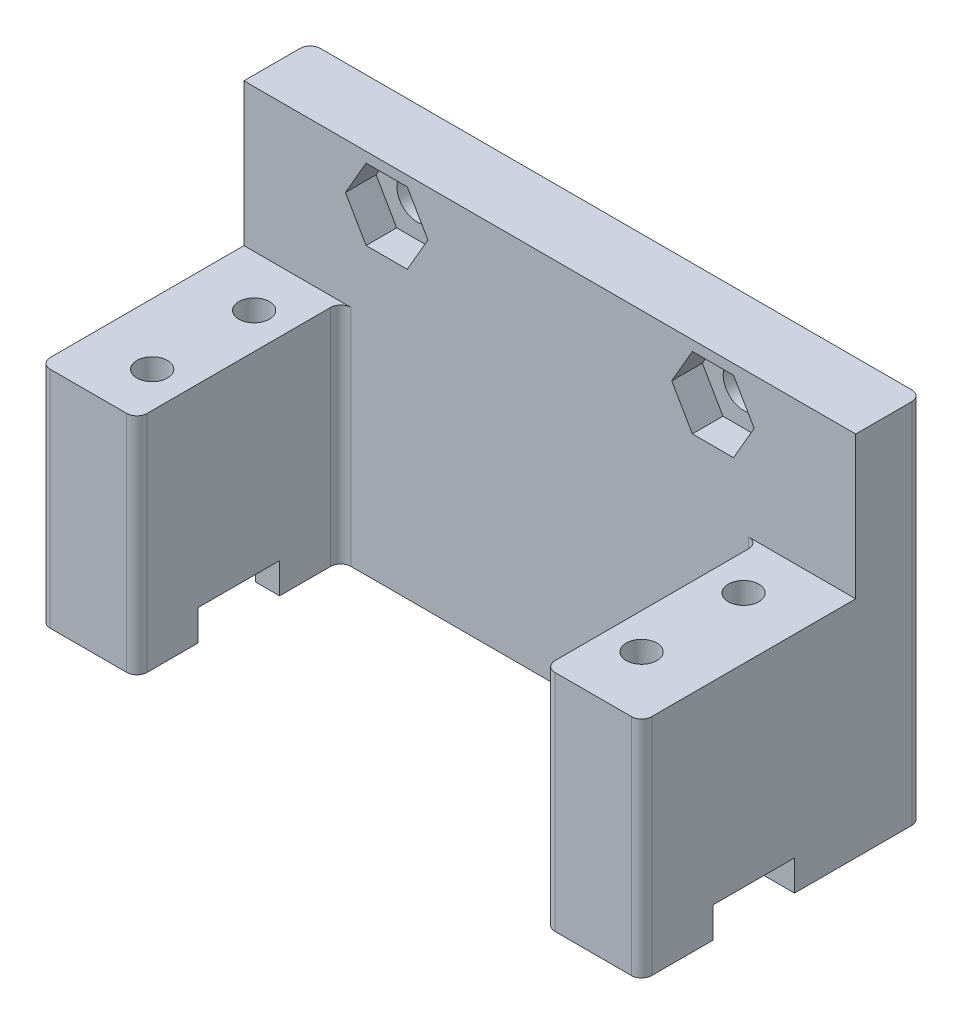
SolidWorks part; units mm, degrees
ref_plane "Front Plane" through (0, 0, 0) normal (0, 0, 1) x (1, 0, 0)
ref_plane "Top Plane" through (0, 0, 0) normal (0, 1, 0) x (1, 0, 0)
ref_plane "Right Plane" through (0, 0, 0) normal (1, 0, 0) x (0, 0, -1)
sketch "Sketch1" plane through (0, 0, 0) normal (0, 0, 1) x (1, 0, 0)
  line L1 (0, 0) -> (60, 0)
  line L2 (0, 0) -> (0, -36)
  line L3 (0, -36) -> (60, -36)
  line L4 (60, 0) -> (60, -36)
  circle A0 centre (14, -4.5) radius 2
  circle A1 centre (46, -4.5) radius 2
  dimension "D3" = 4.5
  dimension "D6" = 4
  dimension "D1" = 60
  dimension "D2" = 36
  dimension "D4" = 14
  dimension "D5" = 2
extrude "Boss-Extrude1" add sketch "Sketch1" along normal blind 6.5
sketch "Sketch2" plane through (0, -36, 0) normal (0, -1, 0) x (1, 0, 0)
  line L1 (0, 6.5) -> (9.5, 6.5)
  line L2 (0, 6.5) -> (0, 26.5)
  line L3 (0, 26.5) -> (9.5, 26.5)
  line L4 (9.5, 6.5) -> (9.5, 26.5)
  line L5 (60, 6.5) -> (50.5, 6.5)
  line L6 (60, 6.5) -> (60, 27.5)
  line L7 (60, 27.5) -> (50.5, 27.5)
  line L8 (50.5, 6.5) -> (50.5, 27.5)
  dimension "D1" = 41
  dimension "D2" = 9.5
  dimension "D3" = 20
extrude "Boss-Extrude2" add sketch "Sketch2" against normal blind 22
sketch "Sketch3" plane through (0, -14, 0) normal (0, 1, 0) x (1, 0, 0)
  line L0 (60, -6.5) -> (0, -6.5) construction
  line L1 (0, -26.5) -> (0, -6.5) construction
  circle A0 centre (6, -11.5) radius 1.5
  circle A1 centre (54, -11.5) radius 1.5
  circle A2 centre (54, -21.5) radius 1.5
  circle A3 centre (6, -21.5) radius 1.5
  dimension "D1" = 2
  dimension "D3" = 5
  dimension "D4" = 6
  dimension "D2" = 2
extrude "Cut-Extrude1" cut sketch "Sketch3" against normal up to next
sketch "Sketch4" plane through (0, 0, 6.5) normal (0, 0, 1) x (1, 0, 0)
  line L1 (11.9793, -1) -> (9.9585, -4.5)
  line L2 (9.9585, -4.5) -> (11.9793, -8)
  line L3 (11.9793, -8) -> (16.0207, -8)
  line L4 (16.0207, -8) -> (18.0415, -4.5)
  line L5 (18.0415, -4.5) -> (16.0207, -1)
  line L6 (16.0207, -1) -> (11.9793, -1)
  circle A0 centre (14, -4.5) radius 3.5 construction
  dimension "D1" = 7
extrude "Cut-Extrude2" cut sketch "Sketch4" against normal blind 3
pattern_linear "LPattern1" count 2 spacing 32 along (1, 0, 0) of "Cut-Extrude2"
fillet "Fillet1" radius 1 8 edges at (50.5, -25, 27.5) (60, -25, 27.5) (9.5, -25, 26.5) (0, -25, 26.5) (50.5, -25, 6.5) (9.5, -25, 6.5) (0, -18, 0) (60, -18, 0)
sketch "Sketch5" plane through (0, 0, 0) normal (0, 1, 0) x (1, 0, 0)
  line L0 (30, 0) -> (30, -17.5)
  line L1 (59, 0) -> (1, 0) construction
  line L2 (30, -17.5) -> (37.5, -17.5)
  line L3 (30, 0) -> (30, 16)
  line L4 (30, 16) -> (37.5, -17.5)
sketch "Sketch6" plane through (60, 0, 0) normal (1, 0, 0) x (0, 0, -1)
  line L0 (-16.5, -14) -> (-16.5, -36)
  line L2 (-26.5, -36) -> (-1, -36) construction
  line L4 (-20.5, -33) -> (-12.5, -33)
  line L5 (-20.5, -33) -> (-20.5, -36)
  line L6 (-20.5, -36) -> (-12.5, -36)
  line L7 (-12.5, -33) -> (-12.5, -36)
  line L8 (-20.5, -33) -> (-12.5, -36) construction
  line L9 (-20.5, -36) -> (-12.5, -33) construction
  point P6 (-16.5, -34.5)
  dimension "D1" = 8
  dimension "D2" = 3
  dimension "D3" = 10
extrude "Cut-Extrude3" cut sketch "Sketch6" against normal through all contours L5 L6 L7 L4
